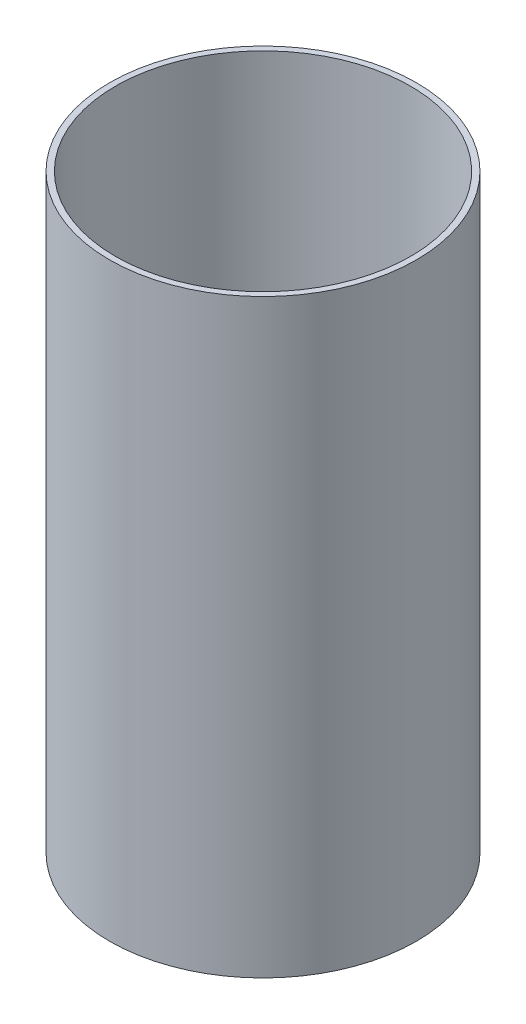
SolidWorks part; units mm, degrees
material "Glass"
ref_plane "Front Plane" through (0, 0, 0) normal (0, 0, 1) x (1, 0, 0)
ref_plane "Top Plane" through (0, 0, 0) normal (0, 1, 0) x (1, 0, 0)
ref_plane "Right Plane" through (0, 0, 0) normal (1, 0, 0) x (0, 0, -1)
sketch "Sketch1" plane through (0, 0, 0) normal (0, 1, 0) x (1, 0, 0)
  circle A0 centre (0, 0) radius 26
  circle A1 centre (0, 0) radius 25
  dimension "D1" = 1
  dimension "D2" = 50
extrude "Boss-Extrude1" add sketch "Sketch1" along normal blind 100
